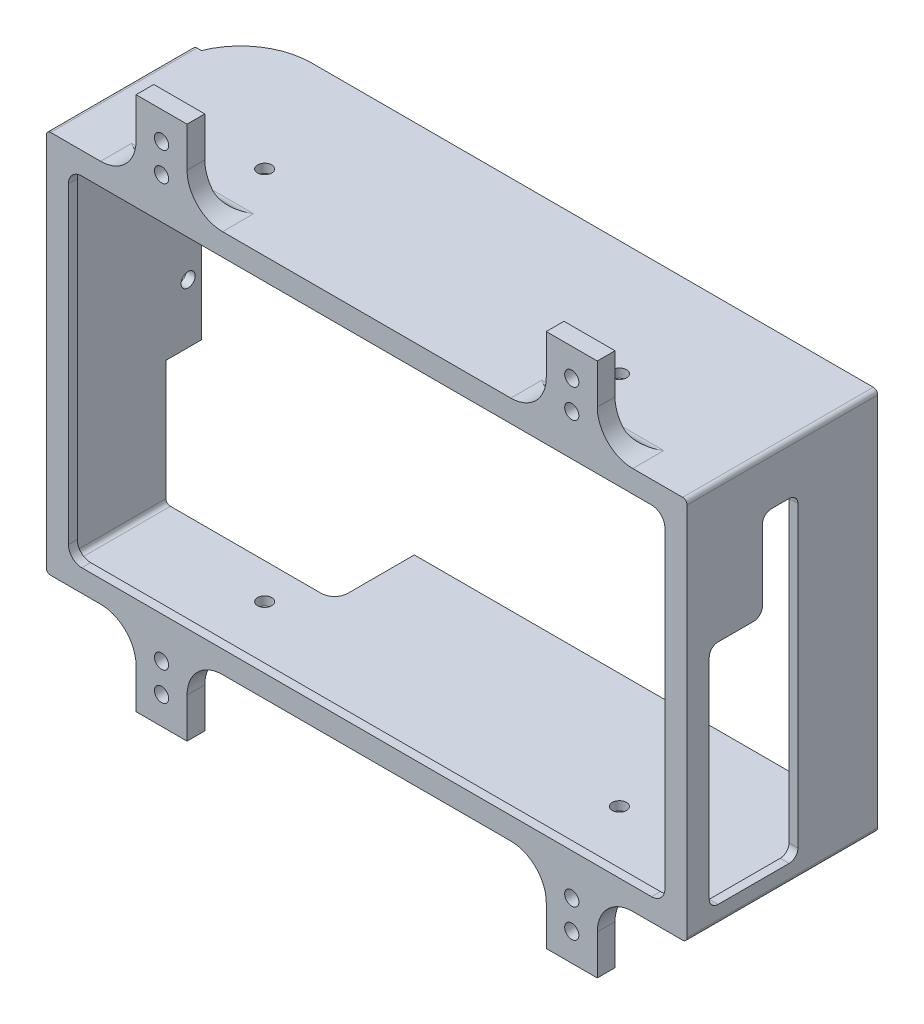
SolidWorks part; units mm, degrees
material "ABS"
ref_plane "前视基准面" through (0, 0, 0) normal (0, 0, 1) x (1, 0, 0)
ref_plane "上视基准面" through (0, 0, 0) normal (0, 1, 0) x (1, 0, 0)
ref_plane "右视基准面" through (0, 0, 0) normal (1, 0, 0) x (0, 0, -1)
other "Configuration Table"
sketch "草图1" plane through (0, 0, 0) normal (0, 0, 1) x (1, 0, 0)
  line L0 (-26.1032, 0) -> (21.1128, 0) construction
  line L1 (0, 15.1629) -> (0, -20.3451) construction
  line L3 (-70.25, -41.25) -> (70.25, -41.25)
  line L4 (-70.25, -41.25) -> (-70.25, 41.25)
  line L5 (-70.25, 41.25) -> (70.25, 41.25)
  line L6 (70.25, -41.25) -> (70.25, 41.25)
  line L7 (-70.25, -41.25) -> (70.25, 41.25) construction
  line L8 (-70.25, 41.25) -> (70.25, -41.25) construction
  point P4 (0, 0)
  dimension "D1" = 140.5
  dimension "D2" = 82.5
extrude "凸台-拉伸1" add sketch "草图1" along normal blind 2
sketch "草图6" plane through (0, 0, 0) normal (0, 0, -1) x (-1, 0, 0)
  line L4 (-70.25, 41.25) -> (-70.25, -41.25)
  line L6 (-70.25, 41.25) -> (-70.25, -41.25)
  line L12 (-72.25, 43.25) -> (-72.25, -43.25)
  line L21 (-72.25, 43.25) -> (-72.25, -43.25)
  line L43 (-72.25, -43.25) -> (72.25, -43.25)
  line L45 (-72.25, -43.25) -> (72.25, -43.25)
  line L47 (70.25, 41.25) -> (-70.25, 41.25)
  line L49 (70.25, 41.25) -> (-70.25, 41.25)
  line L56 (70.25, -41.25) -> (70.25, 41.25)
  line L57 (70.25, -41.25) -> (70.25, 41.25)
  line L58 (-70.25, -41.25) -> (70.25, -41.25)
  line L59 (-70.25, -41.25) -> (70.25, -41.25)
  line L66 (72.25, -43.25) -> (72.25, 43.25)
  line L67 (72.25, -43.25) -> (72.25, 43.25)
  line L68 (72.25, 43.25) -> (-72.25, 43.25)
  line L69 (72.25, 43.25) -> (-72.25, 43.25)
  dimension "D2" = 0
  dimension "D1" = 2
extrude "凸台-拉伸3" add sketch "草图6" along normal blind 41 and the other way blind 2
fillet "圆角2" radius 1 4 edges at (70.25, -41.25, -20.5) (70.25, 41.25, -20.5) (-70.25, -41.25, -20.5) (-70.25, 41.25, -20.5)
fillet "圆角3" radius 1 4 edges at (72.25, 43.25, -19.5) (72.25, -43.25, -19.5) (-72.25, -43.25, -19.5) (-72.25, 43.25, -19.5)
sketch "草图9" plane through (0, 0, 2) normal (0, 0, 1) x (1, 0, 0)
  line L0 (-101.7339, 0) -> (110.1577, 0) construction
  line L1 (0, 49.463) -> (0, -48.599) construction
  circle A14 centre (26.5, -17.5) radius 1.6
  circle A16 centre (0, -17.5) radius 1.6
  circle A17 centre (-10.5, -17) radius 2.1
  circle A18 centre (-26.5, -17.5) radius 1.6
  circle A19 centre (-26.5, 0) radius 1.6
  circle A20 centre (-10.5, 0) radius 2.1
  circle A21 centre (26.5, 0) radius 1.6
  circle A22 centre (10.5, 0) radius 2.1
  circle A23 centre (26.5, 17.5) radius 1.6
  circle A25 centre (0, 17.5) radius 1.6
  circle A26 centre (-10.5, 17) radius 2.1
  circle A27 centre (-26.5, 17.5) radius 1.6
  circle A28 centre (0, 0) radius 1.6
  dimension "D1" = 16
  dimension "D2" = 10.5
  dimension "D3" = 16
  dimension "D4" = 10.5
  dimension "D5" = 17.5
  dimension "D6" = 17.5
  dimension "D7" = 17
  dimension "D8" = 17
  dimension "D9" = 3.2
  dimension "D10" = 4.2
  dimension "D11" = 4.2
extrude "切除-拉伸3" cut sketch "草图9" against normal through all
sketch "草图10" plane through (0, 43.25, 0) normal (0, 1, 0) x (1, 0, 0)
  line L6 (-72.25, 31) -> (-72.25, 41)
  line L7 (-72.25, 41) -> (-55.4176, 41)
  line L8 (-70.25, 31) -> (-72.25, 31)
  arc A1 (-55.4176, 41) -> (-70.25, 31) centre (-55.4176, 25) ccw
  dimension "D1" = 10
  dimension "D2" = 2
  dimension "D3" = 16
extrude "切除-拉伸4" cut sketch "草图10" against normal through all
sketch "草图12" plane through (-72.25, 0, 0) normal (-1, 0, 0) x (0, 0, 1)
  line L1 (-31, -42.25) -> (-31, 42.25) construction
  circle A0 centre (-28, 0) radius 1.6
  dimension "D1" = 3.2
  dimension "D2" = 3
extrude "切除-拉伸5" cut sketch "草图12" against normal up to next
sketch "草图13" plane through (0, 43.25, 0) normal (0, 1, 0) x (1, 0, 0)
  line L0 (0, 49.4247) -> (0, -21.1207) construction
  line L1 (0, 0) -> (54.9564, 0) construction
  line L2 (71.25, -2) -> (71.25, 41) construction
  circle A0 centre (-40, 15) radius 1.6
  circle A1 centre (40, 15) radius 1.6
  dimension "D1" = 80
  dimension "D2" = 15
  dimension "D3" = 3.2
  dimension "D4" = 71.25
extrude "切除-拉伸6" cut sketch "草图13" against normal through all
sketch "草图14" plane through (0, 0, 0) normal (0, 0, -1) x (-1, 0, 0)
  line L0 (-69.25, 41.25) -> (69.25, 41.25) construction
  line L1 (-64.25, 38.25) -> (64.25, 38.25)
  line L2 (-67.25, 35.25) -> (-67.25, -35.25)
  line L3 (-64.25, -38.25) -> (64.25, -38.25)
  line L4 (67.25, 35.25) -> (67.25, -35.25)
  line L5 (70.25, -40.25) -> (70.25, 40.25) construction
  line L6 (-70.25, 40.25) -> (-70.25, -40.25) construction
  line L7 (69.25, -41.25) -> (-69.25, -41.25) construction
  arc A0 (-64.25, 38.25) -> (-67.25, 35.25) centre (-64.25, 35.25) ccw
  arc A1 (-67.25, -35.25) -> (-64.25, -38.25) centre (-64.25, -35.25) ccw
  arc A2 (64.25, -38.25) -> (67.25, -35.25) centre (64.25, -35.25) ccw
  arc A3 (64.25, 38.25) -> (67.25, 35.25) centre (64.25, 35.25) cw
  dimension "D5" = 3
  dimension "D1" = 3
  dimension "D2" = 3
  dimension "D3" = 3
  dimension "D4" = 3
extrude "切除-拉伸7" cut sketch "草图14" against normal blind 10
sketch "草图15" plane through (72.25, 0, 0) normal (1, 0, 0) x (0, 0, -1)
  line L0 (41, 42.25) -> (41, -42.25) construction
  line L1 (15, 12) -> (3, 12)
  line L2 (23, 32) -> (23, -39.25)
  line L3 (23, -39.25) -> (3, -39.25)
  line L4 (3, 12) -> (3, -39.25)
  line L5 (-2, -42.25) -> (41, -42.25) construction
  line L6 (-2, 42.25) -> (-2, -42.25) construction
  line L10 (23, 32) -> (15, 32)
  line L11 (15, 12) -> (15, 32)
  dimension "D1" = 18
  dimension "D2" = 3
  dimension "D3" = 5
  dimension "D4" = 12
  dimension "D5" = 8
  dimension "D6" = 20
extrude "切除-拉伸8" cut sketch "草图15" against normal up to next
fillet "圆角4" radius 2 6 edges at (71.25, -39.25, -23) (71.25, -39.25, -3) (71.25, 12, -3) (71.25, 12, -15) (71.25, 32, -15) (71.25, 32, -23)
sketch "草图18" plane through (0, 0, 2) normal (0, 0, 1) x (1, 0, 0)
  line L0 (71.25, -43.25) -> (-55.4176, -43.25) construction
  line L1 (-40.5, -43.25) -> (-52, -43.25)
  line L2 (-40.5, -43.25) -> (-40.5, -60.25)
  line L3 (-40.5, -60.25) -> (-52, -60.25)
  line L4 (-52, -43.25) -> (-52, -60.25)
  line L5 (0, 75.2716) -> (0, -73.7224) construction
  line L6 (98.6787, 0) -> (-112.9628, 0) construction
  line L7 (52, -43.25) -> (52, -60.25)
  line L8 (40.5, -60.25) -> (52, -60.25)
  line L9 (40.5, -43.25) -> (40.5, -60.25)
  line L10 (40.5, -43.25) -> (52, -43.25)
  line L11 (40.5, 43.25) -> (52, 43.25)
  line L12 (40.5, 43.25) -> (40.5, 60.25)
  line L13 (40.5, 60.25) -> (52, 60.25)
  line L14 (52, 43.25) -> (52, 60.25)
  line L15 (-52, 43.25) -> (-52, 60.25)
  line L16 (-40.5, 60.25) -> (-52, 60.25)
  line L17 (-40.5, 43.25) -> (-40.5, 60.25)
  line L18 (-40.5, 43.25) -> (-52, 43.25)
  dimension "D1" = 17
  dimension "D2" = 40.5
  dimension "D3" = 11.5
extrude "凸台-拉伸4" add sketch "草图18" against normal blind 4
sketch "草图19" plane through (0, 0, -2) normal (0, 0, -1) x (-1, 0, 0)
  line L0 (-100.0575, 0) -> (111.3217, 0) construction
  line L1 (0, 77.6635) -> (0, -73.3216) construction
  circle A0 centre (46.25, 54) radius 1.6
  circle A1 centre (46.25, 47.5) radius 1.6
  circle A2 centre (46.25, -47.5) radius 1.6
  circle A3 centre (46.25, -54) radius 1.6
  circle A4 centre (-46.25, -54) radius 1.6
  circle A5 centre (-46.25, -47.5) radius 1.6
  circle A6 centre (-46.25, 47.5) radius 1.6
  circle A7 centre (-46.25, 54) radius 1.6
  dimension "D1" = 92.5
  dimension "D2" = 6.5
  dimension "D3" = 3.2
  dimension "D4" = 95
extrude "切除-拉伸9" cut sketch "草图19" against normal up to next
sketch "草图20" plane through (0, -43.25, 0) normal (0, -1, 0) x (1, 0, 0)
  line L0 (71.25, -41) -> (-55.4176, -41) construction
  line L6 (-35.25, -49.3161) -> (-67.25, -49.3161)
  line L7 (-32.25, -46.3161) -> (-32.25, -26)
  line L8 (-35.25, -23) -> (-70.25, -23)
  line L14 (-70.25, -23) -> (-70.25, -46.3161)
  line L15 (-71.25, 2) -> (-71.25, -31) construction
  line L16 (-72.25, -31) -> (-72.25, 2) construction
  arc A5 (-35.25, -49.3161) -> (-32.25, -46.3161) centre (-35.25, -46.3161) ccw
  arc A6 (-32.25, -26) -> (-35.25, -23) centre (-35.25, -26) ccw
  arc A10 (-67.25, -49.3161) -> (-70.25, -46.3161) centre (-67.25, -46.3161) cw
  point P9 (-32.25, -49.3161)
  point P12 (-32.25, -23)
  dimension "D4" = 39
  dimension "D2" = 3
  dimension "D3" = 2
  dimension "D1" = 18
extrude "切除-拉伸11" cut sketch "草图20" against normal up to next
fillet "圆角5" radius 8 8 edges at (52, 43.25, 0) (40.5, 43.25, 0) (-52, 43.25, 0) (-40.5, 43.25, 0) (52, -43.25, 0) (40.5, -43.25, 0) (-52, -43.25, 0) (-40.5, -43.25, 0)
fillet "圆角6" radius 3 4 edges at (-46.25, 43.25, -2) (46.25, 43.25, -2) (-46.25, -43.25, -2) (46.25, -43.25, -2)
sketch "草图21" plane through (0, 0, -31) normal (0, 0, -1) x (-1, 0, 0)
  line L0 (35.25, -43.25) -> (70.25, -43.25) construction
  line L1 (61.6056, -13.25) -> (82.985, -13.25)
  line L2 (61.6056, -13.25) -> (61.6056, -43.25)
  line L3 (61.6056, -43.25) -> (82.985, -43.25)
  line L4 (82.985, -13.25) -> (82.985, -43.25)
  dimension "D1" = 30
extrude "切除-拉伸12" cut sketch "草图21" against normal up to surface (8 mm away) up to face at (-56.0914, -41.8914, -23)
